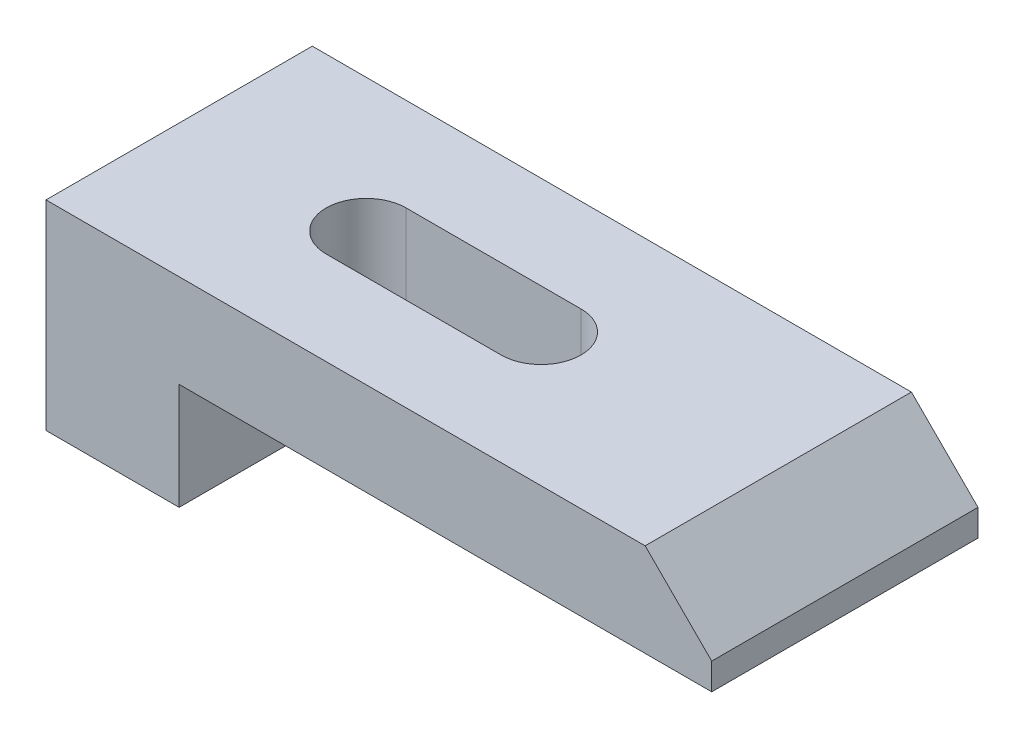
SolidWorks part; units mm, degrees
ref_plane "Front Plane" through (0, 0, 0) normal (0, 0, 1) x (1, 0, 0)
ref_plane "Top Plane" through (0, 0, 0) normal (0, 1, 0) x (1, 0, 0)
ref_plane "Right Plane" through (0, 0, 0) normal (1, 0, 0) x (0, 0, -1)
sketch "Sketch1" plane through (0, 0, 0) normal (0, 0, 1) x (1, 0, 0)
  line L0 (0, 15) -> (0, 8)
  line L2 (0, 8) -> (-40, 8)
  line L3 (-40, 8) -> (-40, 0)
  line L4 (-40, 0) -> (-50, 0)
  line L5 (-50, 0) -> (-50, 15)
  line L6 (-50, 15) -> (0, 15)
  dimension "D1" = 50
  dimension "D2" = 15
  dimension "D4" = 40
  dimension "D6" = 7
extrude "Boss-Extrude1" add sketch "Sketch1" along normal blind 20
chamfer "Chamfer1" distance 5 angle 45 1 edges at (0, 15, 10)
sketch "Sketch2" plane through (0, 15, 0) normal (0, 1, 0) x (1, 0, 0)
  line L0 (-5, -10) -> (-50, -10) construction
  line L1 (-5, -20) -> (-5, 0) construction
  line L2 (-50, -20) -> (-50, 0) construction
  line L3 (-35.9553, -10) -> (-22.8184, -10) construction
  line L4 (-35.9553, -7) -> (-22.8184, -7)
  line L5 (-35.9553, -13) -> (-22.8184, -13)
  arc A0 (-35.9553, -7) -> (-35.9553, -13) centre (-35.9553, -10) ccw
  arc A1 (-22.8184, -13) -> (-22.8184, -7) centre (-22.8184, -10) ccw
  point P8 (-29.3868, -10)
  dimension "D1" = 6
extrude "Cut-Extrude1" cut sketch "Sketch2" against normal blind 20
